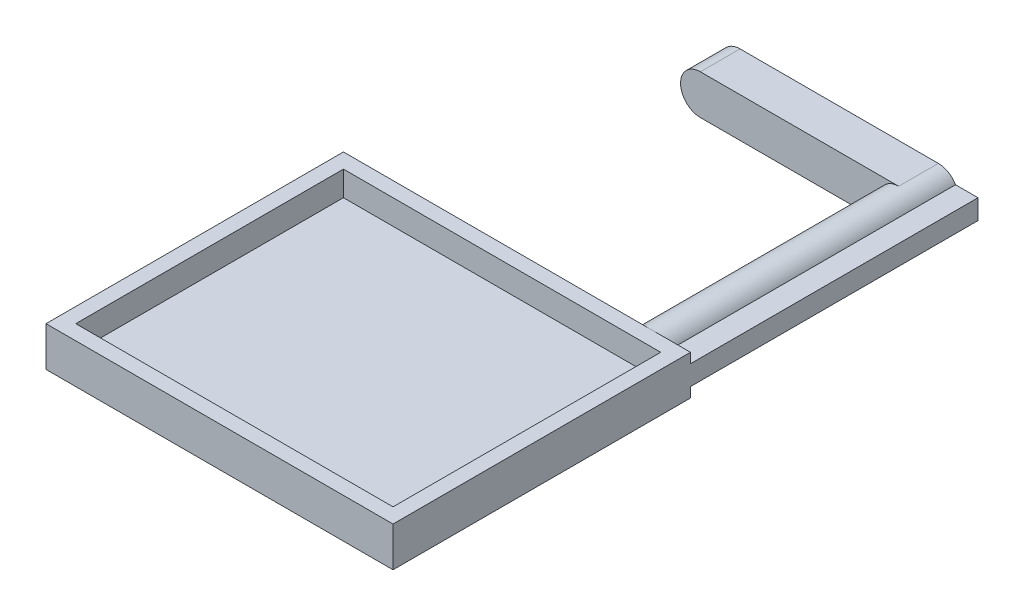
SolidWorks part; units mm, degrees
ref_plane "正面" through (0, 0, 0) normal (0, 0, 1) x (1, 0, 0)
ref_plane "平面" through (0, 0, 0) normal (0, 1, 0) x (1, 0, 0)
ref_plane "右側面" through (0, 0, 0) normal (1, 0, 0) x (0, 0, -1)
sketch "ｽｹｯﾁ1" plane through (0, 0, 0) normal (0, 0, 1) x (1, 0, 0)
  line L0 (3.4641, 2) -> (8, 2)
  line L1 (8, 2) -> (8, -2)
  line L2 (8, -2) -> (3.4641, -2)
  arc A1 (3.4641, 2) -> (3.4641, -2) centre (0, 0) ccw
  point P4 (8, 0)
  dimension "D1" = 4
  dimension "D2" = 4
  dimension "D3" = 8
extrude "ﾎﾞｽ - 押し出し1" add sketch "ｽｹｯﾁ1" against normal blind 50 and the other way blind 5
sketch "ｽｹｯﾁ2" plane through (0, 0, -50) normal (0, 0, -1) x (-1, 0, 0)
  circle A0 centre (0, 0) radius 2.1
  dimension "D1" = 4.2
extrude "ｶｯﾄ - 押し出し1" cut sketch "ｽｹｯﾁ2" against normal through all
sketch "ｽｹｯﾁ13" plane through (0, 0, 5) normal (0, 0, 1) x (1, 0, 0)
  circle A0 centre (0, 0) radius 8.4706
extrude "ｶｯﾄ - 押し出し6" cut sketch "ｽｹｯﾁ13" against normal blind 5
sketch "ｽｹｯﾁ15" plane through (0, 0, -50) normal (0, 0, -1) x (-1, 0, 0)
  line L0 (40, 0) -> (0, 0) construction
  line L1 (40, -4) -> (0, -4)
  line L2 (40, 4) -> (0, 4)
  arc A0 (40, -4) -> (40, 4) centre (40, 0) ccw
  arc A1 (0, 4) -> (0, -4) centre (0, 0) ccw
  arc A3 (-3.4641, -2) -> (-3.4641, 2) centre (0, 0) ccw construction
  point P3 (20, 0)
  dimension "D1" = 40
extrude "ﾎﾞｽ - 押し出し4" add sketch "ｽｹｯﾁ15" along normal blind 8
sketch "ｽｹｯﾁ18" plane through (0, 0, -58) normal (0, 0, -1) x (-1, 0, 0)
  line L0 (40, 4) -> (0, 4) construction
  line L1 (0, 0) -> (20, 0) construction
  line L2 (20, 0) -> (40, 0) construction
  circle A0 centre (0, 0) radius 3.1
  circle A1 centre (40, 0) radius 3.1
  arc A2 (40, -4) -> (40, 4) centre (40, 0) ccw construction
  arc A3 (0, 4) -> (0, -4) centre (0, 0) ccw construction
  circle A4 centre (20, 0) radius 3.1
  circle A7 centre (10, 0) radius 3.1
  circle A8 centre (30, 0) radius 3.1
  point P17 (20, 4)
  point P21 (10, 0)
  point P23 (30, 0)
  dimension "D1" = 6.2
extrude "ｶｯﾄ - 押し出し7" cut sketch "ｽｹｯﾁ18" against normal blind 3.05
sketch "ｽｹｯﾁ19" plane through (0, 0, -58) normal (0, 0, -1) x (-1, 0, 0)
  line L0 (0, 0) -> (20, 0)
  line L1 (20, 0) -> (40, 0)
sketch "ｽｹｯﾁ20" plane through (0, 0, -50) normal (0, 0, -1) x (-1, 0, 0)
  line L0 (-8, 2) -> (-3.4641, 2) construction
  line L1 (-3.4641, 2) -> (-8, 2)
  line L2 (-8, 2) -> (-8, -2)
  line L3 (-8, -2) -> (-3.4641, -2)
  arc A0 (-3.4641, -2) -> (-3.4641, 2) centre (0, 0) cw
  arc A1 (0, 4) -> (0, -4) centre (0, 0) ccw construction
extrude "ﾎﾞｽ - 押し出し5" add sketch "ｽｹｯﾁ20" along normal up to surface (8 mm away) up to face at (-3.1, 0, -58)
sketch "ｽｹｯﾁ21" plane through (0, 0, 0) normal (0, 0, 1) x (1, 0, 0)
  line L1 (8, 4) -> (-62, 4)
  line L2 (8, 4) -> (8, -4)
  line L3 (8, -4) -> (-62, -4)
  line L4 (-62, 4) -> (-62, -4)
  line L5 (8, -2) -> (8, 2) construction
  arc A0 (3.4641, 2) -> (3.4641, -2) centre (0, 0) ccw construction
  dimension "D1" = 70
extrude "ﾎﾞｽ - 押し出し6" add sketch "ｽｹｯﾁ21" along normal blind 60
sketch "ｽｹｯﾁ22" plane through (0, 4, 0) normal (0, 1, 0) x (1, 0, 0)
  line L1 (5, -3) -> (-59, -3)
  line L2 (5, -3) -> (5, -57)
  line L3 (5, -57) -> (-59, -57)
  line L4 (-59, -3) -> (-59, -57)
  line L6 (-62, -60) -> (-62, 0) construction
  line L7 (8, -60) -> (8, 0) construction
  line L8 (0, 0) -> (-62, 0) construction
  line L9 (8, -60) -> (-62, -60) construction
  dimension "D1" = 3
  dimension "D2" = 3
  dimension "D3" = 3
  dimension "D4" = 3
extrude "ｶｯﾄ - 押し出し8" cut sketch "ｽｹｯﾁ22" against normal blind 5
